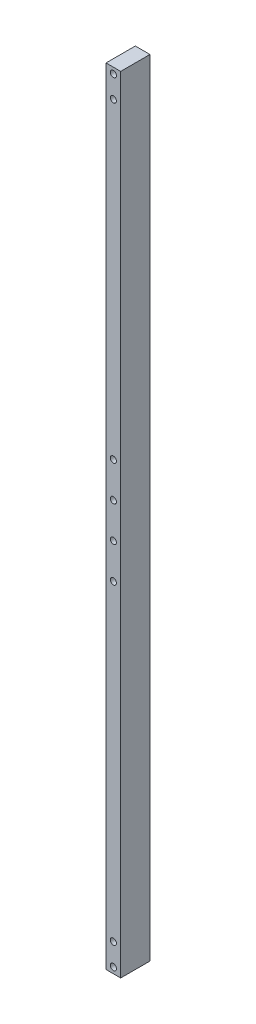
SolidWorks part; units mm, degrees
ref_plane "前视基准面" through (0, 0, 0) normal (0, 0, 1) x (1, 0, 0)
ref_plane "上视基准面" through (0, 0, 0) normal (0, 1, 0) x (1, 0, 0)
ref_plane "右视基准面" through (0, 0, 0) normal (1, 0, 0) x (0, 0, -1)
sketch "草图1" plane through (0, 0, 0) normal (0, 1, 0) x (1, 0, 0)
  line L1 (-3.0928, 14.8196) -> (6.9072, 14.8196)
  line L2 (-3.0928, 14.8196) -> (-3.0928, -5.1804)
  line L3 (-3.0928, -5.1804) -> (6.9072, -5.1804)
  line L4 (6.9072, 14.8196) -> (6.9072, -5.1804)
  dimension "D1" = 10
  dimension "D2" = 20
extrude "凸台-拉伸1" add sketch "草图1" along normal blind 600
sketch "草图2" plane through (0, 0, 5.1804) normal (0, 0, 1) x (1, 0, 0)
  line L0 (1.9072, 600) -> (1.9072, 300) construction
  line L1 (-3.0928, 600) -> (6.9072, 600) construction
  line L2 (1.9072, 300) -> (1.9072, 288) construction
  line L3 (1.9072, 288) -> (1.9072, 264) construction
  line L4 (1.9072, 300) -> (17.8891, 300) construction
  circle A1 centre (1.9072, 264) radius 2.1
  circle A2 centre (1.9072, 288) radius 2.1
  circle A3 centre (1.9072, 312) radius 2.1
  circle A4 centre (1.9072, 336) radius 2.1
  dimension "D2" = 24
  dimension "D4" = 4.2
  dimension "D5" = 4.2
  dimension "D1" = 300
  dimension "D3" = 12
sketch "草图6" plane through (0, 0, -14.8196) normal (0, 0, -1) x (-1, 0, 0)
  line L0 (-1.9072, 600) -> (-1.9072, 590) construction
  line L1 (-6.9072, 600) -> (3.0928, 600) construction
  line L3 (-6.9072, 600) -> (13.0928, 600)
  line L4 (-6.9072, 600) -> (-6.9072, 590)
  line L5 (-6.9072, 590) -> (13.0928, 590)
  line L6 (13.0928, 600) -> (13.0928, 590)
  dimension "D1" = 10
  dimension "D2" = 20
extrude "切除-拉伸4" cut sketch "草图6" against normal blind 50
sketch "草图7" plane through (0, 0, -14.8196) normal (0, 0, -1) x (-1, 0, 0)
  line L0 (-1.9072, 0) -> (-1.9072, 14.2817) construction
  line L1 (-6.9072, 0) -> (3.0928, 0) construction
  line L2 (-6.9072, 590) -> (-6.9072, 0) construction
  line L3 (3.0928, 0) -> (-6.9072, 0)
  line L4 (3.0928, 0) -> (3.0928, 10)
  line L5 (3.0928, 10) -> (-6.9072, 10)
  line L6 (-6.9072, 0) -> (-6.9072, 10)
  dimension "D1" = 10
extrude "切除-拉伸5" cut sketch "草图7" against normal blind 82
extrude "切除-拉伸6" cut sketch "草图2" against normal through all
sketch "草图8" plane through (0, 0, 5.1804) normal (0, 0, 1) x (1, 0, 0)
  line L0 (1.9072, 590) -> (1.9072, 564) construction
  line L1 (6.9072, 590) -> (-3.0928, 590) construction
  line L2 (1.9072, 590) -> (1.9072, 549) construction
  line L3 (6.9072, 300) -> (-69.4205, 300) construction
  line L4 (6.9072, 590) -> (6.9072, 10) construction
  circle A0 centre (1.9072, 564) radius 2.1
  circle A1 centre (1.9072, 549) radius 2.1
  circle A2 centre (1.9072, 36) radius 2.1
  circle A3 centre (1.9072, 51) radius 2.1
  circle A4 centre (1.9072, 583) radius 2.1
  circle A5 centre (1.9072, 17) radius 2.1
  dimension "D3" = 4.2
  dimension "D4" = 4.2
  dimension "D5" = 4.2
  dimension "D1" = 26
  dimension "D2" = 15
  dimension "D6" = 7
extrude "切除-拉伸7" cut sketch "草图8" against normal blind 54
sketch "草图9" plane through (0, 0, 5.1804) normal (0, 0, 1) x (1, 0, 0)
  line L4 (1.9072, 17) -> (1.9072, 31) construction
  line L5 (6.9072, 10) -> (-3.0928, 10)
  line L6 (6.9072, 10) -> (6.9072, 32)
  line L7 (-3.0928, 10) -> (-3.0928, 32)
  line L8 (6.9072, 32) -> (-3.0928, 32)
  line L10 (-3.0928, 300) -> (77.7871, 300) construction
  line L11 (-3.0928, 590) -> (-3.0928, 10) construction
  line L12 (-3.0928, 590) -> (-3.0928, 568)
  line L13 (6.9072, 568) -> (-3.0928, 568)
  line L14 (6.9072, 590) -> (6.9072, 568)
  line L15 (6.9072, 590) -> (-3.0928, 590)
  dimension "D1" = 14
  dimension "D2" = 22
extrude "切除-拉伸8" cut sketch "草图9" against normal through all
equation "\"200、\"=87"
equation "\"47。5\"=39.4923"
